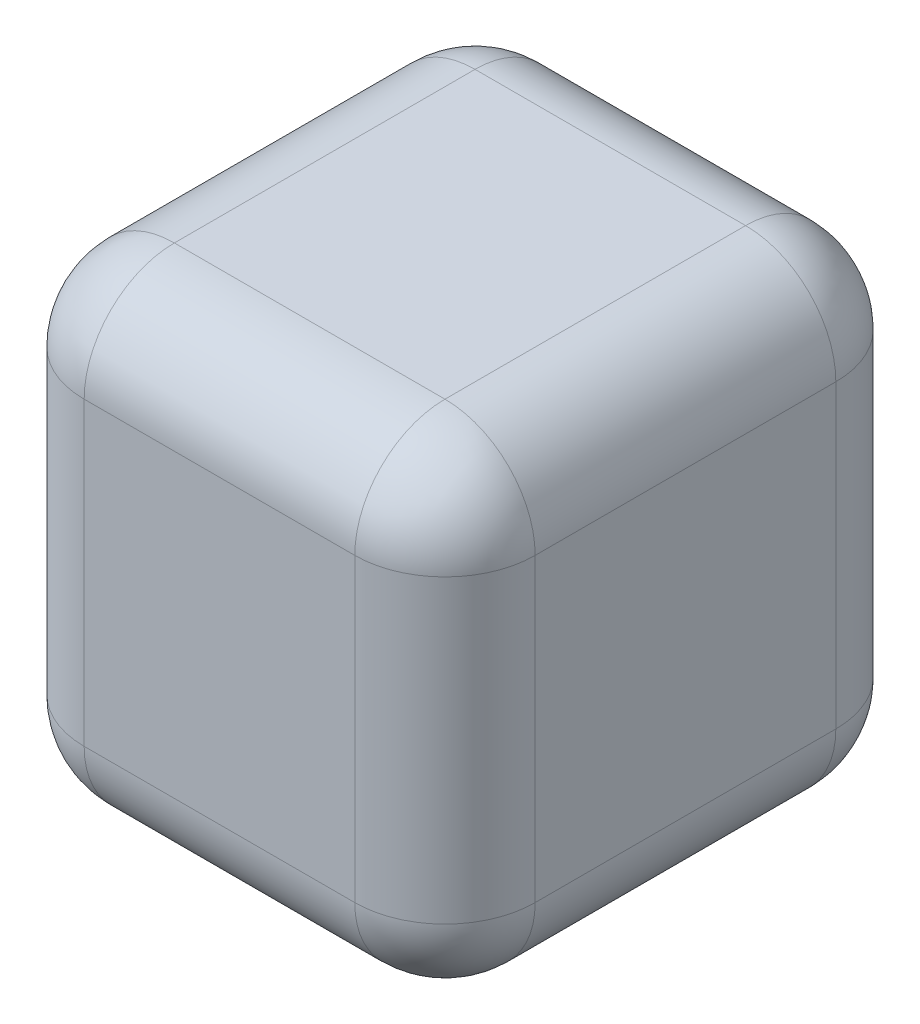
SolidWorks part; units mm, degrees
material "ABS"
ref_plane "Front Plane" through (0, 0, 0) normal (0, 0, 1) x (1, 0, 0)
ref_plane "Top Plane" through (0, 0, 0) normal (0, 1, 0) x (1, 0, 0)
ref_plane "Right Plane" through (0, 0, 0) normal (1, 0, 0) x (0, 0, -1)
ref_plane "X_WEB" through (33.5, 0, 0) normal (1, 0, 0) x (0, 0, -1)
sketch "Sketch1" plane through (33.5, 0, 0) normal (1, 0, 0) x (0, 0, -1)
  line L1 (-16, -16) -> (16, -16)
  line L2 (-16, -16) -> (-16, 16)
  line L3 (-16, 16) -> (16, 16)
  line L4 (16, -16) -> (16, 16)
extrude "Boss-Extrude1" add sketch "Sketch1" along normal blind 30
fillet "Fillet1" radius 6 12 edges at (33.5, 0, 16) (33.5, -16, 0) (33.5, 0, -16) (33.5, 16, 0) (63.5, 0, 16) (63.5, -16, 0) (63.5, 0, -16) (63.5, 16, 0) (48.5, 16, 16) (48.5, 16, -16) (48.5, -16, -16) (48.5, -16, 16)
sketch "Sketch2" plane through (33.5, 0, 0) normal (1, 0, 0) x (0, 0, -1)
  circle A0 centre (-4.5, -4.5) radius 0.8
  circle A1 centre (4.5, -4.5) radius 0.8
  circle A2 centre (-4.5, 4.5) radius 0.8
  circle A3 centre (4.5, 4.5) radius 0.8
extrude "Cut-Extrude2" cut sketch "Sketch2" along normal blind 6
